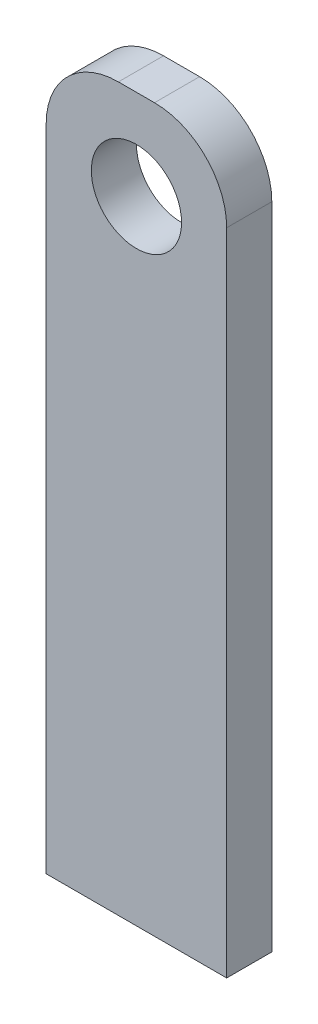
SolidWorks part; units mm, degrees
material "6061-T6 (SS)"
ref_plane "Front Plane" through (0, 0, 0) normal (0, 0, 1) x (1, 0, 0)
ref_plane "Top Plane" through (0, 0, 0) normal (0, 1, 0) x (1, 0, 0)
ref_plane "Right Plane" through (0, 0, 0) normal (1, 0, 0) x (0, 0, -1)
sketch "Sketch1" plane through (0, 0, 0) normal (0, 0, 1) x (1, 0, 0)
  line L1 (-6.35, -25.4) -> (6.35, -25.4)
  line L2 (-6.35, -25.4) -> (-6.35, 25.4)
  line L3 (-6.35, 25.4) -> (6.35, 25.4)
  line L4 (6.35, -25.4) -> (6.35, 25.4)
  line L5 (-6.35, -25.4) -> (6.35, 25.4) construction
  line L6 (-6.35, 25.4) -> (6.35, -25.4) construction
  point P0 (0, 0)
  dimension "D1" = 50.8
  dimension "D2" = 12.7
extrude "Extrude1" add sketch "Sketch1" along normal blind 3.175
sketch "Sketch2" plane through (0, 0, 3.175) normal (0, 0, 1) x (1, 0, 0)
  line L0 (0, 25.4) -> (0, 19.05) construction
  line L1 (6.35, 25.4) -> (-6.35, 25.4) construction
  dimension "D1" = 6.35
hole_wizard "1/4 (0.25) Diameter Hole1" positions "3DSketch1" profile "Sketch5" hole size "1/4" standard "Ansi Inch"
sketch3d "3DSketch1"
  point P0 (0, 19.05, 3.175)
sketch "Sketch5" plane through (0, 19.05, 3.175) normal (1, 0, 0) x (0, -1, 0)
  line L0 (0, 0) -> (0, 8.2577)
  line L1 (0, 8.2577) -> (3.175, 6.35)
  line L2 (3.175, 6.35) -> (3.175, 0)
  line L5 (3.175, 0) -> (0, 0)
  line L10 (0, 8.2577) -> (-3.175, 6.35) construction
  line L11 (0, -6.35) -> (0, 107.95) construction
  dimension "Hole Dia." = 6.35
  dimension "Hole Depth" = 6.35
  dimension "Drill Angle" = 118
fillet "Fillet1" radius 5.08 2 edges at (6.35, 25.4, 1.5875) (-6.35, 25.4, 1.5875)
